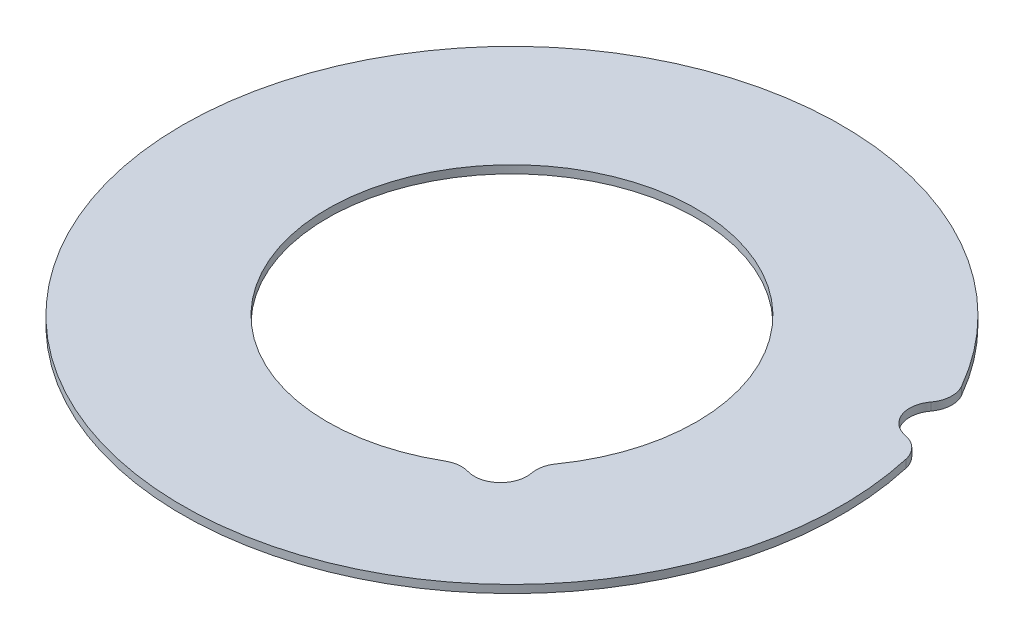
SolidWorks part; units mm, degrees
ref_plane "Front Plane" through (0, 0, 0) normal (0, 0, 1) x (1, 0, 0)
ref_plane "Top Plane" through (0, 0, 0) normal (0, 1, 0) x (1, 0, 0)
ref_plane "Right Plane" through (0, 0, 0) normal (1, 0, 0) x (0, 0, -1)
sketch "Sketch1" plane through (0, 0, 0) normal (0, 0, 1) x (1, 0, 0)
  line L0 (0, 0) -> (0, 26.6785) construction
  line L1 (-12.5, 0) -> (-12.5, 0.3)
  line L2 (-12.5, 0.3) -> (-7, 0.3)
  line L5 (-7, 0.3) -> (-7, 0)
  line L6 (-7, 0) -> (-12.5, 0)
  dimension "D1" = 5.5
  dimension "D2" = 12.5
  dimension "D3" = 0.3
revolve "Revolve1" add sketch "Sketch1" angle 360 about L0
sketch "Sketch2" plane through (0, 0.3, 0) normal (0, 1, 0) x (1, 0, 0)
  circle A0 centre (4.5711, -5) radius 1
  circle A1 centre (11.5892, 4.5) radius 1
  dimension "D1" = 2
extrude "Cut-Extrude1" cut sketch "Sketch2" against normal blind 10
fillet "Fillet1" radius 1 4 edges at (11.9769, 0.15, -3.5782) (11.2533, 0.15, -5.4419) (3.9468, 0.15, 5.7812) (5.405, 0.15, 4.4481)
